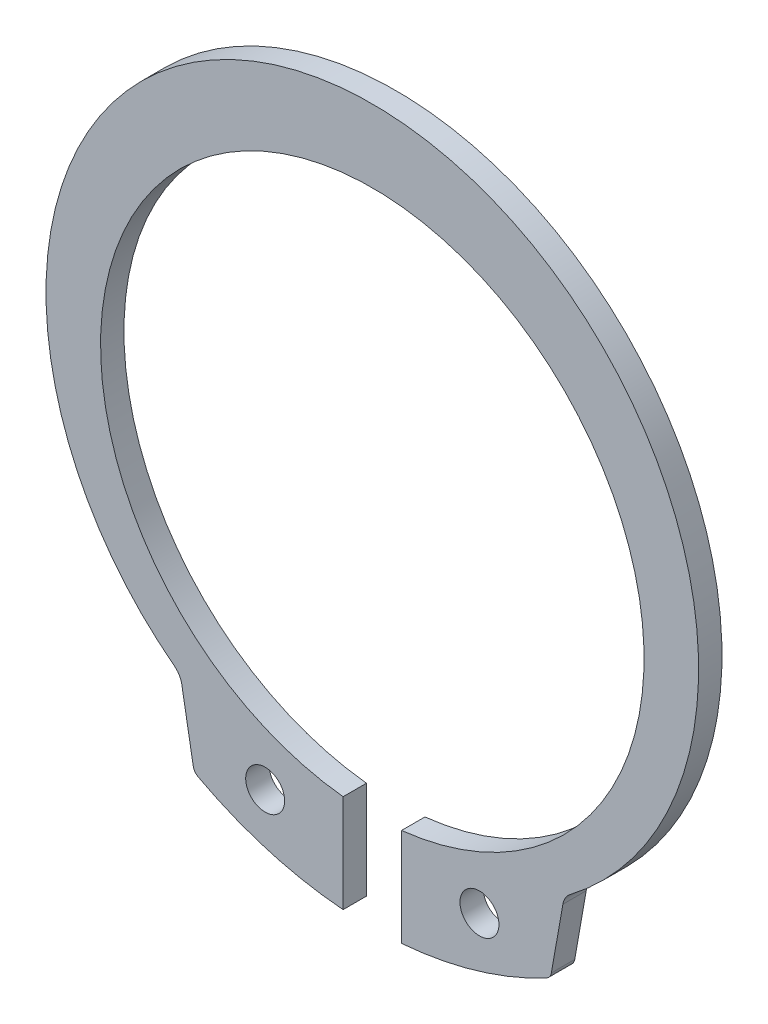
SolidWorks part; units mm, degrees
ref_plane "Front" through (0, 0, 0) normal (0, 0, 1) x (1, 0, 0)
ref_plane "Top" through (0, 0, 0) normal (0, 1, 0) x (1, 0, 0)
ref_plane "Right" through (0, 0, 0) normal (1, 0, 0) x (0, 0, -1)
sketch "Sketch1" plane through (0, 0, 0) normal (0, 0, 1) x (1, 0, 0)
  line L0 (0, 4.2365) -> (0, -4.9012) construction
  line L1 (-1.5, -14.7991) -> (-1.5, -19.8205)
  line L2 (1.5, -14.7991) -> (1.5, -19.8205)
  line L3 (16.5, -0.93) -> (-16.5, -0.93) construction
  line L4 (9.8507, -13.5472) -> (9.1493, -17.525)
  line L7 (-9.8507, -13.5472) -> (-9.1493, -17.525)
  line L8 (-9.8507, -13.5472) -> (-9.8507, -21.6179) construction
  arc A0 (1.5, -14.7991) -> (-1.5, -14.7991) centre (0, -0.93) ccw
  arc A1 (9.8507, -13.5472) -> (-9.8507, -13.5472) centre (0, 0) ccw
  arc A2 (-16.5, -0.93) -> (16.5, -0.93) centre (0, -0.93) ccw construction
  arc A3 (9.1493, -17.525) -> (1.5, -19.8205) centre (0, -0.93) cw
  arc A4 (-9.1493, -17.525) -> (-1.5, -19.8205) centre (0, -0.93) ccw
  circle A5 centre (5.5, -16.4863) radius 1
  circle A6 centre (-5.5, -16.4863) radius 1
  point P17 (-9.5, -15.5361)
  dimension "d" = 27.9
  dimension "D2" = 10
  dimension "d0" = 33.5
  dimension "d1" = 2
  dimension "R1" = 16.5
  dimension "R" = 18.95
  dimension "B1" = 3
  dimension "C" = 0.93
  dimension "L" = 19
  dimension "B2" = 11
extrude "Body" add sketch "Sketch1" against normal blind 1.2
fillet "Fillet1" radius 0.5 2 edges at (-9.1493, -17.525, -0.6) (9.1493, -17.525, -0.6)
fillet "Fillet2" radius 1 2 edges at (9.8507, -13.5472, -0.6) (-9.8507, -13.5472, -0.6)
